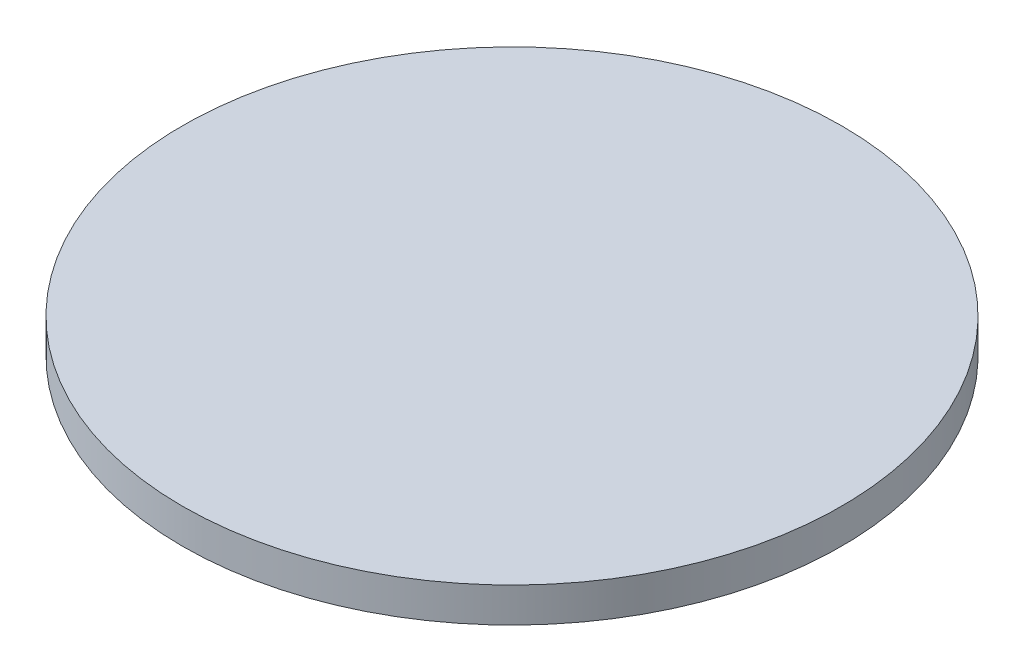
SolidWorks part; units mm, degrees
ref_plane "Front Plane" through (0, 0, 0) normal (0, 0, 1) x (1, 0, 0)
ref_plane "Top Plane" through (0, 0, 0) normal (0, 1, 0) x (1, 0, 0)
ref_plane "Right Plane" through (0, 0, 0) normal (1, 0, 0) x (0, 0, -1)
sketch "Sketch1" plane through (0, 0, 0) normal (0, 1, 0) x (1, 0, 0)
  circle A0 centre (0, 0) radius 14.25
  dimension "D1" = 28.5
extrude "Boss-Extrude1" add sketch "Sketch1" along normal blind 1.5 contours A0
